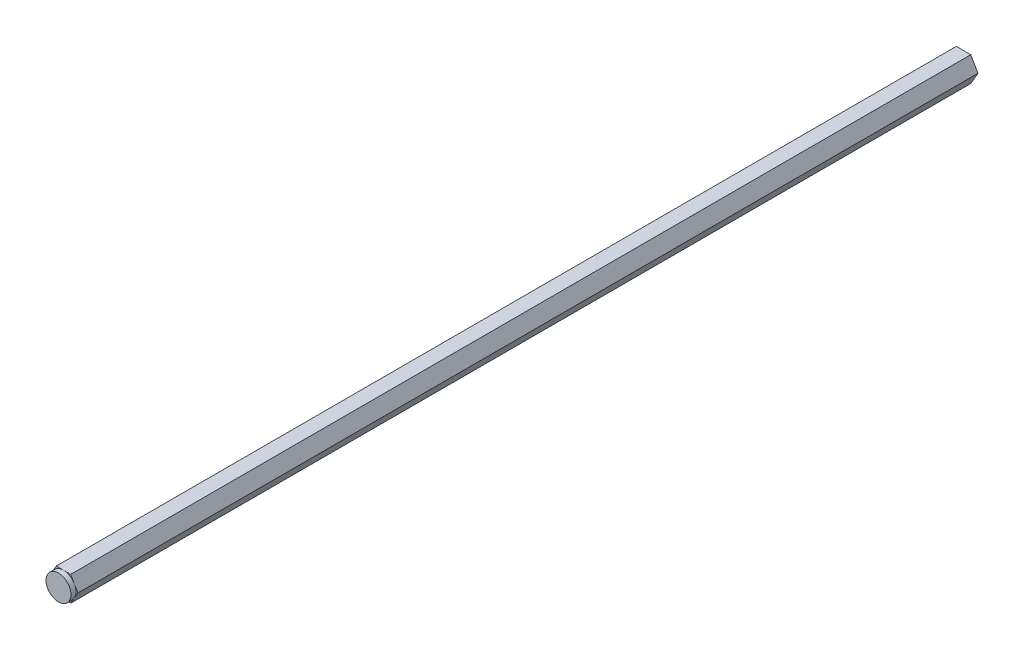
SolidWorks part; units mm, degrees
ref_plane "Front Plane" through (0, 0, 0) normal (0, 0, 1) x (1, 0, 0)
ref_plane "Top Plane" through (0, 0, 0) normal (0, 1, 0) x (1, 0, 0)
ref_plane "Right Plane" through (0, 0, 0) normal (1, 0, 0) x (0, 0, -1)
sketch "Sketch1" plane through (0, 0, 0) normal (0, 0, 1) x (1, 0, 0)
  line L1 (7.3323, 0) -> (3.6662, 6.35)
  line L2 (3.6662, 6.35) -> (-3.6662, 6.35)
  line L3 (-3.6662, 6.35) -> (-7.3323, 0)
  line L4 (-7.3323, 0) -> (-3.6662, -6.35)
  line L5 (-3.6662, -6.35) -> (3.6662, -6.35)
  line L6 (3.6662, -6.35) -> (7.3323, 0)
  circle A0 centre (0, 0) radius 6.35 construction
extrude "Boss-Extrude1" add sketch "Sketch1" along normal blind 457.2
sketch "Sketch2" plane through (0, 0, 457.2) normal (0, 0, 1) x (1, 0, 0)
  circle A0 centre (0, 0) radius 6.35
extrude "Boss-Extrude2" add sketch "Sketch2" along normal blind 2.54
